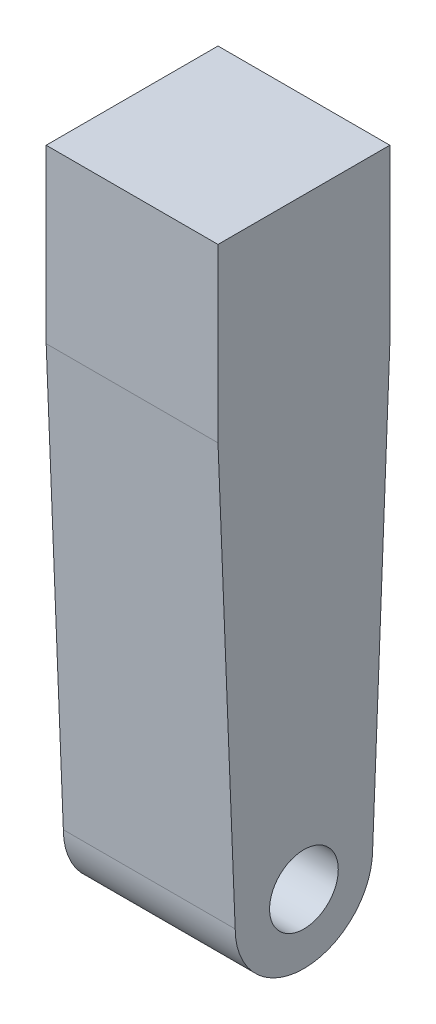
SolidWorks part; units mm, degrees
material "PLA"
ref_plane "Alzado" through (0, 0, 0) normal (0, 0, 1) x (1, 0, 0)
ref_plane "Planta" through (0, 0, 0) normal (0, 1, 0) x (1, 0, 0)
ref_plane "Vista lateral" through (0, 0, 0) normal (1, 0, 0) x (0, 0, -1)
sketch "Croquis1" plane through (0, 0, 0) normal (1, 0, 0) x (0, 0, -1)
  line L0 (0, 0) -> (0, -7.5) construction
  line L1 (1.25, 1.25) -> (-1.25, 1.25)
  line L2 (1.25, 1.25) -> (1.25, -1.25)
  line L4 (-1.25, 1.25) -> (-1.25, -1.25)
  line L5 (1.25, 1.25) -> (-1.25, -1.25) construction
  line L6 (1.25, -1.25) -> (-1.25, 1.25) construction
  line L7 (-1, -7.5) -> (-1.25, -1.25)
  line L8 (1.25, -1.25) -> (1, -7.5)
  circle A0 centre (0, -7.5) radius 0.5
  arc A1 (-1, -7.5) -> (1, -7.5) centre (0, -7.5) ccw
  point P0 (0, 0)
  dimension "D4" = 1
  dimension "D5" = 2
  dimension "D6" = 1.25
  dimension "D1" = 2.5
  dimension "D2" = 2.5
  dimension "D3" = 7.5
extrude "Saliente-Extruir1" add sketch "Croquis1" along normal blind 2.5
sketch "Croquis2" plane through (0, 1.25, 0) normal (0, 1, 0) x (1, 0, 0)
  line L0 (0, 0) -> (2.5, 0) construction
  line L1 (0, 1.25) -> (0, -1.25) construction
  line L2 (2.5, 1.25) -> (2.5, -1.25) construction
